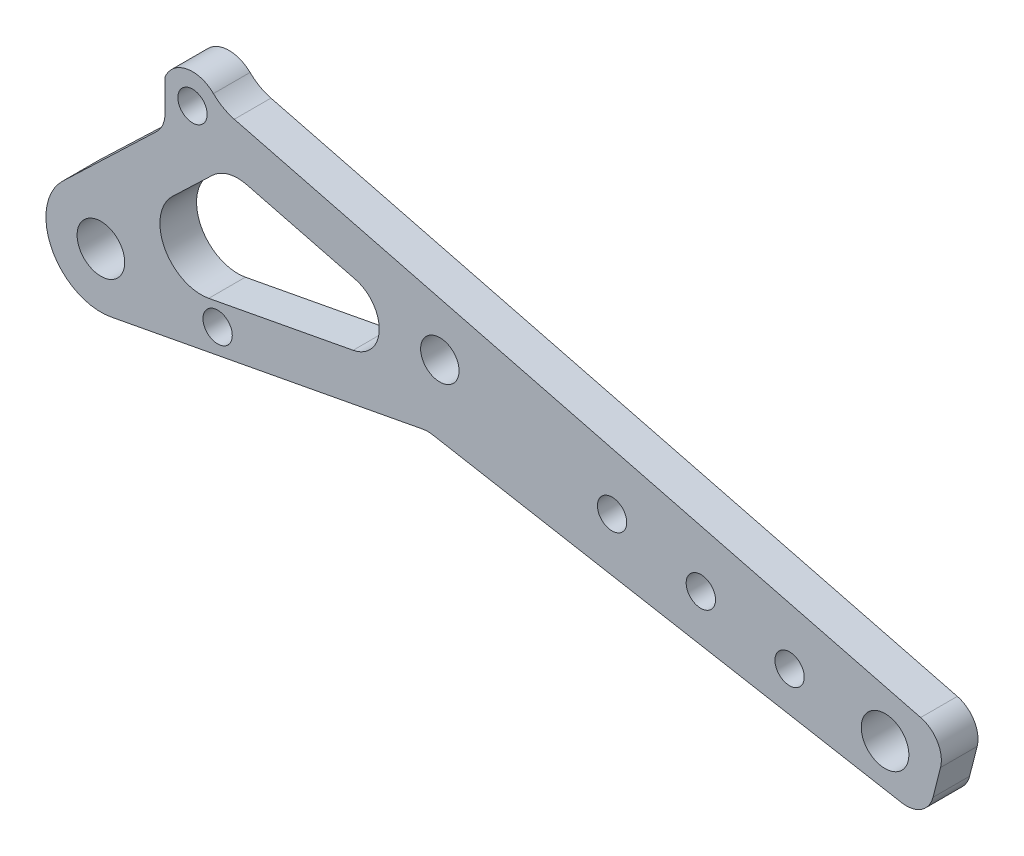
SolidWorks part; units mm, degrees
material "Thornel Mat VMA"
ref_plane "Front" through (0, 0, 0) normal (0, 0, 1) x (1, 0, 0)
ref_plane "Top" through (0, 0, 0) normal (0, 1, 0) x (1, 0, 0)
ref_plane "Right" through (0, 0, 0) normal (1, 0, 0) x (0, 0, -1)
sketch "草图1" plane through (0, 0, 0) normal (0, 0, 1) x (1, 0, 0)
  line L0 (-30, 15) -> (-30, 8)
  line L1 (-30, 8) -> (-3.6258, -6.5654)
  line L5 (-1.324, -7.3822) -> (30, -13)
  line L6 (30, -13) -> (40, -13)
  line L7 (41.2348, -3.1549) -> (-8.8909, 9.6201)
  line L8 (-8.8909, 9.6201) -> (-30, 15)
  line L9 (0, 0) -> (40, -8) construction
  circle A0 centre (0, 0) radius 2.1
  arc A1 (-3.6258, -6.5654) -> (-1.324, -7.3822) centre (0, 0) ccw
  arc A2 (40, -13) -> (41.2348, -3.1549) centre (40, -8) ccw
  dimension "D1" = 4.2
  dimension "D2" = 30
  dimension "D5" = 15
  dimension "D6" = 10
  dimension "D7" = 40
  dimension "D3" = 15
  dimension "D4" = 7
  dimension "D8" = 30
  dimension "D9" = 8
extrude "凸台-拉伸1" add sketch "草图1" along normal blind 4
fillet "圆角3" radius 5 1 edges at (30, -13, 2)
sketch "草图2" plane through (0, 0, 4) normal (0, 0, 1) x (1, 0, 0)
  line L0 (41.2348, -3.1549) -> (38.3436, -14.4994)
  line L1 (38.3436, -14.4994) -> (44.0794, -18.4254)
  line L2 (44.0794, -18.4254) -> (50.6504, -6.6756)
  line L3 (50.6504, -6.6756) -> (42.4734, -0.7779)
  line L4 (42.4734, -0.7779) -> (41.2348, -3.1549)
  line L5 (41.2348, -3.1549) -> (-30, 15) construction
extrude "切除-拉伸1" cut sketch "草图2" against normal through all
sketch "草图5" plane through (0, 0, 4) normal (0, 0, 1) x (1, 0, 0)
  line L0 (-27, 13.75) -> (-27.8025, 17.8485)
  line L1 (-27.8025, 17.8485) -> (-34.2001, 16.5958)
  line L2 (-34.2001, 16.5958) -> (-34.2001, 10.5)
  line L4 (-30.25, 10.5) -> (-34.2001, 10.5)
  circle A0 centre (-27, 10.5) radius 1.6
  arc A1 (-27, 13.75) -> (-30.25, 10.5) centre (-27, 10.5) ccw
  circle A2 centre (0, 0) radius 2.1 construction
  dimension "D1" = 3.2
  dimension "D2" = 6.5
  dimension "D3" = 27
  dimension "D4" = 10.5
extrude "切除-拉伸4" cut sketch "草图5" against normal through all
sketch "草图6" plane through (0, 0, 4) normal (0, 0, 1) x (1, 0, 0)
  line L2 (-1.324, -7.3822) -> (-35.8888, -13.8962)
  line L3 (-30, 8) -> (-30, 7)
  line L5 (-30, 8) -> (-1.324, -7.3822)
  line L6 (-30, 7) -> (-41.1476, -3.6644)
  arc A0 (-41.1476, -3.6644) -> (-35.8888, -13.8962) centre (-37, -8) ccw
  circle A1 centre (0, 0) radius 2.1 construction
  circle A2 centre (-27, 10.5) radius 1.6 construction
  circle A3 centre (-37, -8) radius 2.6
  dimension "D1" = 12
  dimension "D4" = 5.2
  dimension "D2" = 8
  dimension "D3" = 10
  dimension "D5" = 1
extrude "凸台-拉伸3" add sketch "草图6" against normal blind 4
fillet "圆角4" radius 3 4 edges at (41.2348, -3.1549, 2) (38.7257, -13, 2) (-1.324, -7.3822, 2) (-30, 7, 2)
sketch "草图12" plane through (0, 0, 0) normal (0, 0, -1) x (-1, 0, 0)
  line L0 (-38.3278, -2.414) -> (-55.7702, -6.8594)
  line L2 (-53.1472, -17.1513) -> (-28.9128, -12.805)
  line L3 (0.7809, -7.4796) -> (-29.5622, -12.9215) construction
  line L4 (-38.3278, -2.414) -> (-28.9128, -12.805)
  line L5 (-38.3278, -2.414) -> (27.1, 14.2609) construction
  line L7 (-55.7702, -6.8594) -> (-53.1472, -17.1513)
  line L9 (-40.4939, -6.062) -> (-39.3015, -10.7409) construction
  dimension "D1" = 15
extrude "凸台-拉伸6" add sketch "草图12" against normal through all
sketch "草图8" plane through (0, 0, 0) normal (0, 0, -1) x (-1, 0, 0)
  line L0 (-55.7702, -6.8594) -> (27.1, 14.2609) construction
  line L1 (-28.494, -7.6475) -> (-18.8037, -5.1778) construction
  line L2 (-38.1842, -10.1171) -> (-28.494, -7.6475) construction
  line L3 (0, 0) -> (-1.76, 6.9057) construction
  line L5 (-18.8037, -5.1778) -> (-20.656, 2.0898) construction
  circle A1 centre (-18.8037, -5.1778) radius 1.6
  circle A3 centre (-28.494, -7.6475) radius 1.6
  circle A4 centre (-38.1842, -10.1171) radius 1.6
  dimension "D2" = 3.2
  dimension "D3" = 3.2
  dimension "D4" = 10
  dimension "D6" = 3.2
  dimension "D7" = 10
  dimension "D1" = 7.5
  dimension "D5" = 19.5
extrude "切除-拉伸5" cut sketch "草图8" against normal through all
sketch "草图9" plane through (0, 0, 0) normal (0, 0, -1) x (-1, 0, 0)
  line L0 (30, 11.75) -> (30, 25.8799)
  line L2 (-55.3997, -8.3129) -> (27.4705, 12.8074)
  line L3 (-59.9786, -9.4799) -> (22.4376, 11.5247)
  line L5 (30, 25.8799) -> (-59.9786, 25.8799)
  line L6 (-59.9786, 25.8799) -> (-59.9786, -9.4799)
  arc A0 (30, 11.75) -> (24.7163, 12.8124) centre (27, 10.5) ccw
  arc A2 (22.4376, 11.5247) -> (24.7163, 12.8124) centre (21.2028, 16.3698) ccw
  dimension "D2" = 5
  dimension "D1" = 1.5
extrude "切除-拉伸6" cut sketch "草图9" against normal through all
sketch "草图10" plane through (0, 0, 0) normal (0, 0, -1) x (-1, 0, 0)
  line L0 (30, 11.75) -> (30, 9.25)
  arc A0 (30, 11.75) -> (30, 9.25) centre (27, 10.5) ccw
  circle A1 centre (27, 10.5) radius 1.6
  dimension "D1" = 3.2
extrude "凸台-拉伸5" add sketch "草图10" against normal through all
sketch "草图11" plane through (0, 0, 0) normal (0, 0, -1) x (-1, 0, 0)
  line L5 (-55.3997, -8.3129) -> (22.4376, 11.5247) construction
  line L6 (1.8661, -7.4844) -> (35.8888, -13.8962) construction
  line L8 (24.825, 5.0311) -> (29.1692, 0.8753)
  line L10 (30.9262, 6.114) -> (41.1476, -3.6644) construction
  line L14 (9.2466, 3.003) -> (21.0721, 6.0169)
  line L17 (9.4628, -3.828) -> (25.2251, -6.7985)
  arc A0 (9.4628, -3.828) -> (9.2466, 3.003) centre (10.111, -0.3886) cw
  arc A1 (29.1692, 0.8753) -> (25.2251, -6.7985) centre (26.0584, -2.3764) cw
  arc A2 (24.825, 5.0311) -> (21.0721, 6.0169) centre (22.0599, 2.1408) ccw
  dimension "D2" = 5
  dimension "D3" = 5
  dimension "D4" = 3.5
  dimension "D5" = 4.5
  dimension "D6" = 4
  dimension "D1" = 5
extrude "切除-拉伸7" cut sketch "草图11" against normal through all
fillet "圆角5" radius 3 2 edges at (53.1472, -17.1513, 2) (55.3997, -8.3129, 2)
sketch "草图13" plane through (0, 0, 0) normal (0, 0, -1) x (-1, 0, 0)
  line L0 (-52.4927, -7.572) -> (22.4376, 11.5247) construction
  circle A0 centre (-48.6059, -11.7412) radius 2.6
  dimension "D1" = 5.2
  dimension "D2" = 5
extrude "切除-拉伸8" cut sketch "草图13" against normal blind 10
sketch "草图14" plane through (0, 0, 4) normal (0, 0, 1) x (1, 0, 0)
  circle A0 centre (-24.2579, -9.0247) radius 1.6
  dimension "D1" = 3.2
extrude "切除-拉伸9" cut sketch "草图14" against normal blind 10
